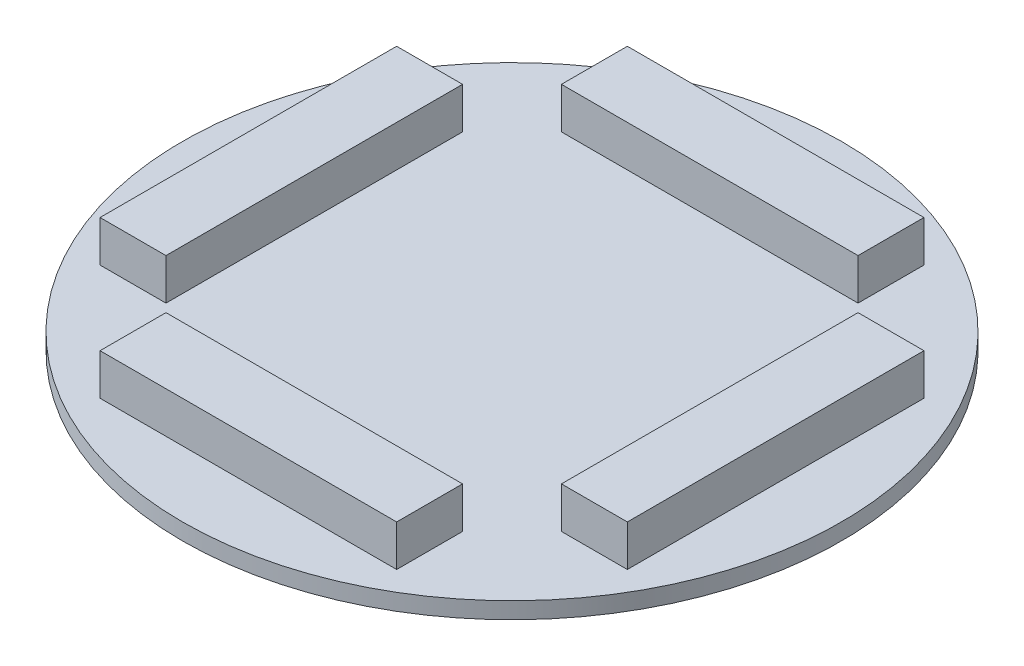
SolidWorks part; units mm, degrees
material "A-Glass Fiber"
ref_plane "Front Plane" through (0, 0, 0) normal (0, 0, 1) x (1, 0, 0)
ref_plane "Top Plane" through (0, 0, 0) normal (0, 1, 0) x (1, 0, 0)
ref_plane "Right Plane" through (0, 0, 0) normal (1, 0, 0) x (0, 0, -1)
sketch "Sketch1" plane through (0, 0, 0) normal (0, 1, 0) x (1, 0, 0)
  circle A0 centre (0, 0) radius 20
  dimension "D1" = 40
extrude "PCB" add sketch "Sketch1" along normal blind 1
sketch "Sketch2" plane through (0, 1, 0) normal (0, 1, 0) x (1, 0, 0)
  line L0 (0, 20) -> (0, 0) construction
  line L1 (-9, 16) -> (9, 16)
  line L2 (-9, 16) -> (-9, 12)
  line L3 (-9, 12) -> (9, 12)
  line L4 (9, 16) -> (9, 12)
  circle A0 centre (0, 0) radius 20 construction
  point P9 (0, 16)
  dimension "D1" = 4
  dimension "D2" = 18
  dimension "D3" = 16
extrude "Hirose Connector Stack" add sketch "Sketch2" along normal blind 2.5 contours L1 L4 L3 L2
pattern_circular "CirPattern1" count 4 over 360 about axis through (0, 0, 0) along (0, 1, 0) of "Hirose Connector Stack"
